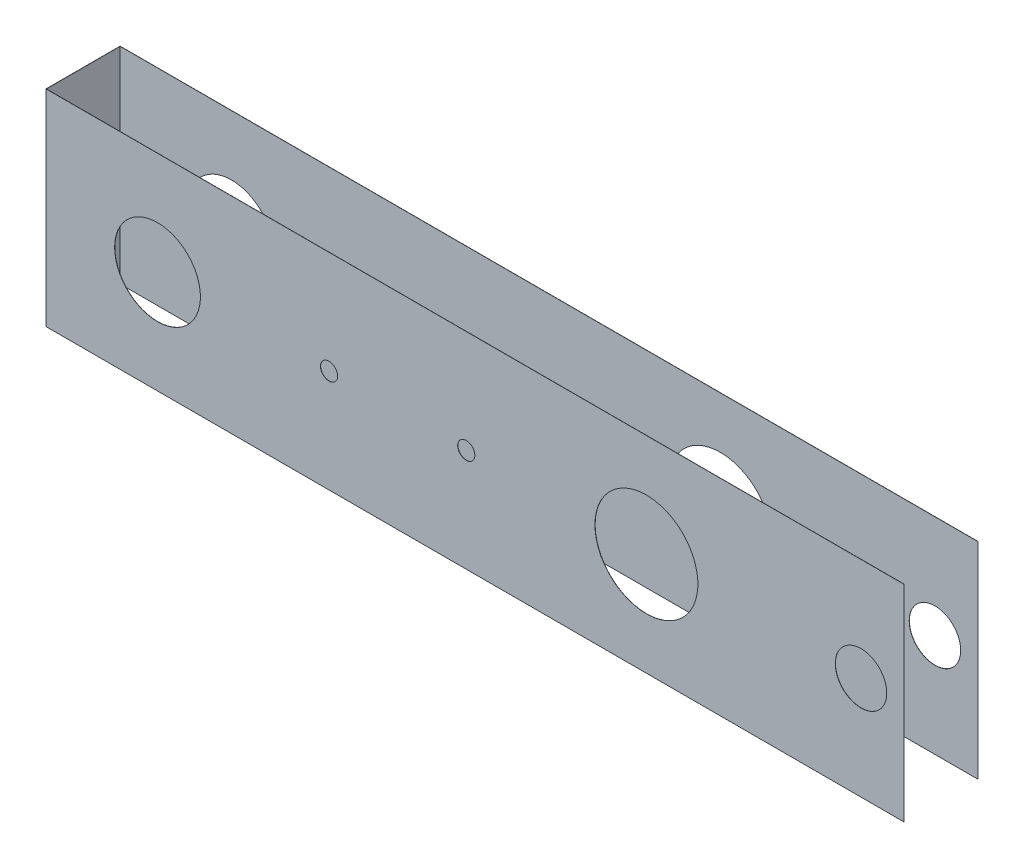
SolidWorks part; units mm, degrees
ref_plane "前视基准面" through (0, 0, 0) normal (0, 0, 1) x (1, 0, 0)
ref_plane "上视基准面" through (0, 0, 0) normal (0, 1, 0) x (1, 0, 0)
ref_plane "右视基准面" through (0, 0, 0) normal (1, 0, 0) x (0, 0, -1)
sketch "草图1" plane through (0, 0, 0) normal (0, 1, 0) x (1, 0, 0)
  line L0 (815.7222, 138.3355) -> (315.6222, 138.3355)
  line L1 (315.6222, 138.3355) -> (315.6222, 95.1355)
  line L2 (315.6222, 95.1355) -> (815.7222, 95.1355)
  line L3 (815.7222, 95.1355) -> (815.7222, 95.2355)
  line L4 (815.7222, 95.2355) -> (315.7222, 95.2355)
  line L5 (315.7222, 95.2355) -> (315.7222, 138.2355)
  line L6 (315.7222, 138.2355) -> (815.7222, 138.2355)
  line L7 (815.7222, 138.2355) -> (815.7222, 138.3355)
  line L8 (315.7222, 116.7355) -> (923.0996, 116.7355) construction
  point P10 (0, 0)
  dimension "D1" = 500
  dimension "D2" = 0.1
  dimension "D3" = 0.1
  dimension "D4" = 43
  dimension "D5" = 500
extrude "凸台-拉伸1" add sketch "草图1" along normal blind 120
ref_plane "基准面1" through (0, 0, -138.3355) normal (0, 0, -1) x (-1, 0, 0)
sketch "草图2" plane through (0, 0, -138.3355) normal (0, 0, -1) x (-1, 0, 0)
  circle A0 centre (-380.6222, 60) radius 25
  circle A1 centre (-480.6222, 60) radius 5
  circle A2 centre (-560.6222, 60) radius 5
  circle A3 centre (-665.6222, 60) radius 30
  circle A4 centre (-790.7222, 60) radius 15
  dimension "D2" = 50
  dimension "D4" = 10
  dimension "D6" = 10
  dimension "D8" = 60
  dimension "D1" = 30
extrude "切除-拉伸1" cut sketch "草图2" against normal blind 120
